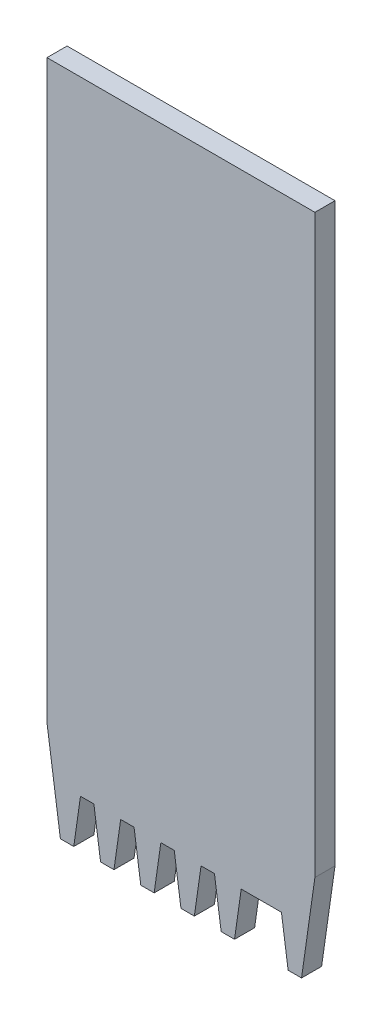
SolidWorks part; units mm, degrees
ref_plane "Front Plane" through (0, 0, 0) normal (0, 0, 1) x (1, 0, 0)
ref_plane "Top Plane" through (0, 0, 0) normal (0, 1, 0) x (1, 0, 0)
ref_plane "Right Plane" through (0, 0, 0) normal (1, 0, 0) x (0, 0, -1)
sketch "Sketch1" plane through (0, 0, 0) normal (0, 0, 1) x (1, 0, 0)
  line L0 (0, 0) -> (0, 50) construction
  line L1 (0, 50) -> (20, 50) construction
  line L2 (20, 50) -> (20, 0) construction
  line L3 (20, 0) -> (0, 0) construction
  line L5 (0, 5) -> (20, 5) construction
  line L6 (1.5, 3.5) -> (1.5, 0) construction
  line L7 (4.5, 3.5) -> (4.5, 0) construction
  line L8 (7.5, 3.5) -> (7.5, 0) construction
  line L9 (10.5, 3.5) -> (10.5, 0) construction
  line L10 (13.5, 3.5) -> (13.5, 0) construction
  line L11 (18.5, 3.5) -> (18.5, 0) construction
  line L12 (0, 3.5) -> (20, 3.5) construction
  line L13 (1.5, 1.75) -> (4.5, 1.75) construction
  line L14 (4.5, 1.75) -> (7.5, 1.75) construction
  line L17 (7.5, 1.75) -> (10.5, 1.75) construction
  line L18 (0, 7) -> (1, 0)
  line L24 (1, 0) -> (2, 0)
  line L26 (2, 0) -> (2.5, 3.5)
  line L29 (2.5, 3.5) -> (3.5, 3.5)
  line L30 (3.5, 3.5) -> (4, 0)
  line L31 (4, 0) -> (5, 0)
  line L32 (5, 0) -> (5.5, 3.5)
  line L33 (5.5, 3.5) -> (6.5, 3.5)
  line L34 (6.5, 3.5) -> (7, 0)
  line L35 (7, 0) -> (8, 0)
  line L36 (8, 0) -> (8.5, 3.5)
  line L37 (8.5, 3.5) -> (9.5, 3.5)
  line L38 (9.5, 3.5) -> (10, 0)
  line L39 (10, 0) -> (11, 0)
  line L40 (11, 0) -> (11.5, 3.5)
  line L41 (11.5, 3.5) -> (12.5, 3.5)
  line L45 (0, 7) -> (0, 50)
  line L46 (0, 50) -> (20, 50)
  line L47 (20, 50) -> (20, 7)
  line L48 (10, 50) -> (10, 5) construction
  line L49 (12.5, 3.5) -> (13, 0)
  line L51 (13, 0) -> (14, 0)
  line L52 (14, 0) -> (14.5, 3.5)
  line L53 (14.5, 3.5) -> (17.5, 3.5)
  line L54 (17.5, 3.5) -> (18, 0)
  line L55 (18, 0) -> (19, 0)
  line L56 (19, 0) -> (20, 7)
  line L57 (10.5, 1.75) -> (13.5, 1.75) construction
  line L58 (13.5, 1.75) -> (18.5, 1.75) construction
  line L61 (1.5, 1.75) -> (0, 1.75) construction
  line L62 (18.5, 1.75) -> (20, 1.75) construction
  dimension "D7" = 1
  dimension "D2" = 5
  dimension "D3" = 45
  dimension "D4" = 3
  dimension "D5" = 1
  dimension "D6" = 5
  dimension "D8" = 1.5
  dimension "D9" = 20
  dimension "D10" = 50
  dimension "D11" = 3.5
extrude "Boss-Extrude1" add sketch "Sketch1" along normal blind 1.5
